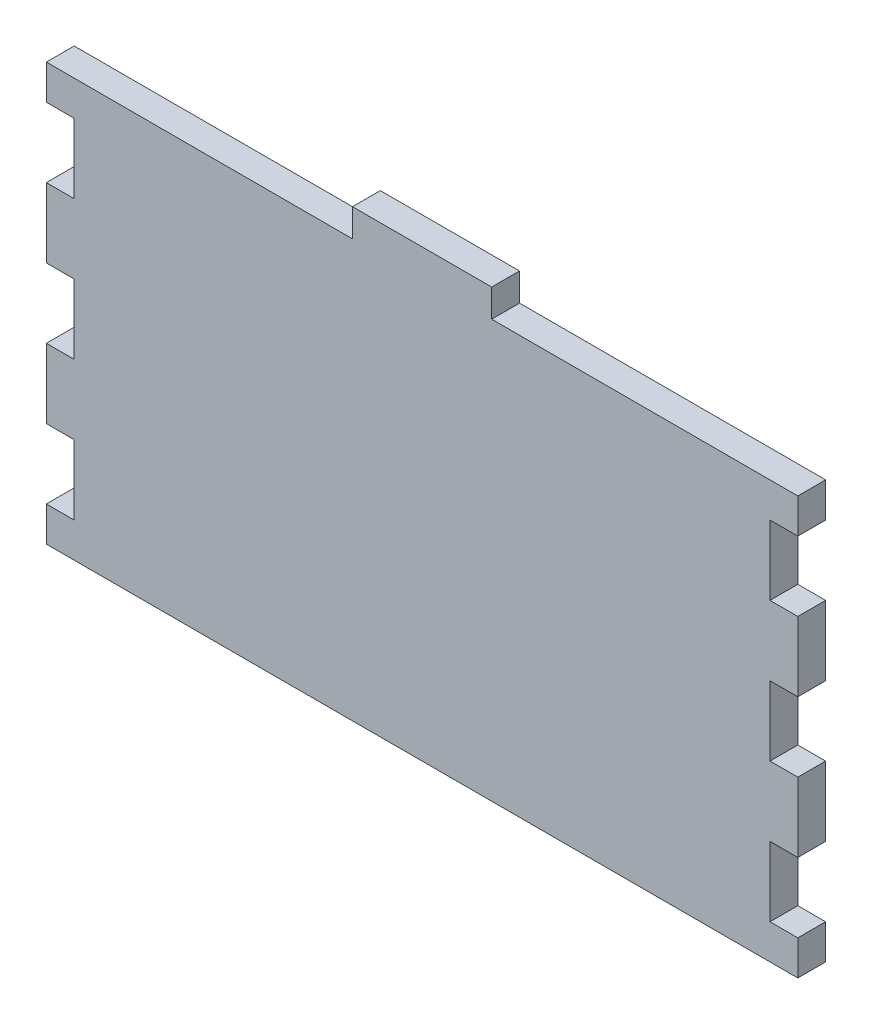
SolidWorks part; units mm, degrees
ref_plane "Front Plane" through (0, 0, 0) normal (0, 0, 1) x (1, 0, 0)
ref_plane "Top Plane" through (0, 0, 0) normal (0, 1, 0) x (1, 0, 0)
ref_plane "Right Plane" through (0, 0, 0) normal (1, 0, 0) x (0, 0, -1)
sketch "Sketch1" plane through (0, 0, 0) normal (0, 0, 1) x (1, 0, 0)
  line L0 (-50, 30) -> (-40, 30)
  line L1 (-50, -30) -> (50, -30)
  line L2 (-50, -30) -> (-50, 30)
  line L3 (-50, 30) -> (50, 30)
  line L4 (50, -30) -> (50, 30)
  line L5 (0, 30) -> (0, -30) construction
  line L6 (-50, 0) -> (50, 0) construction
  line L7 (-40, 30) -> (-30, 30)
  line L8 (-30, 30) -> (-20, 30)
  line L9 (-20, 30) -> (-10, 30)
  line L10 (-10, 30) -> (0, 30)
  line L11 (0, 30) -> (10, 30)
  line L12 (10, 30) -> (20, 30)
  line L13 (20, 30) -> (30, 30)
  line L14 (30, 30) -> (40, 30)
  line L15 (40, 30) -> (50, 30)
  line L16 (50, 30) -> (50, 20)
  line L17 (50, 20) -> (50, 10)
  line L18 (50, 10) -> (50, 6.1062)
  line L19 (50, 6.1062) -> (50, 0)
  line L20 (50, 0) -> (50, -10)
  line L21 (50, -10) -> (50, -20)
  line L22 (50, -20) -> (50, -25.2212)
  line L23 (50, -25.2212) -> (50, -30)
  line L24 (-50, 30) -> (-50, 20)
  line L25 (-50, 20) -> (-50, 10)
  line L26 (-50, 10) -> (-50, -10)
  line L27 (-50, -10) -> (-50, -20)
  line L29 (-50, 30) -> (-54, 30)
  line L30 (-50, 30) -> (-50, 25)
  line L31 (-50, 25) -> (-54, 25)
  line L32 (-54, 30) -> (-54, 25)
  line L33 (-50, 15) -> (-54, 15)
  line L34 (-50, 15) -> (-50, 5)
  line L35 (-50, 5) -> (-54, 5)
  line L36 (-54, 15) -> (-54, 5)
  line L37 (-50, -5) -> (-54, -5)
  line L38 (-50, -5) -> (-50, -15)
  line L39 (-50, -15) -> (-54, -15)
  line L40 (-54, -5) -> (-54, -15)
  line L41 (-50, -30) -> (-54, -30)
  line L42 (-50, -30) -> (-50, -25)
  line L43 (-50, -25) -> (-54, -25)
  line L44 (-54, -30) -> (-54, -25)
  line L45 (50, 30) -> (54, 30)
  line L46 (50, 30) -> (50, 25)
  line L47 (50, 25) -> (54, 25)
  line L48 (54, 30) -> (54, 25)
  line L65 (50, 15) -> (54, 15)
  line L66 (50, 15) -> (50, 5)
  line L67 (50, 5) -> (54, 5)
  line L68 (54, 15) -> (54, 5)
  line L69 (50, -5) -> (54, -5)
  line L70 (50, -5) -> (50, -15)
  line L71 (50, -15) -> (54, -15)
  line L72 (54, -5) -> (54, -15)
  line L73 (50, -30) -> (54, -30)
  line L74 (50, -30) -> (50, -25)
  line L75 (50, -25) -> (54, -25)
  line L76 (54, -30) -> (54, -25)
  point P0 (0, 0)
  dimension "D1" = 60
  dimension "D2" = 100
  dimension "D3" = 10
  dimension "D4" = 10
  dimension "D5" = 10
  dimension "D6" = 10
  dimension "D7" = 10
  dimension "D8" = 10
  dimension "D9" = 10
  dimension "D10" = 10
  dimension "D11" = 10
  dimension "D12" = 0
  dimension "D13" = 10
  dimension "D14" = 10
  dimension "D15" = 10
  dimension "D16" = 10
  dimension "D17" = 10
  dimension "D18" = 10
  dimension "D19" = 10
  dimension "D20" = 10
  dimension "D21" = 4
  dimension "D22" = 4
  dimension "D23" = 4
  dimension "D24" = 4
  dimension "D25" = 5
  dimension "D26" = 5
  dimension "D27" = 10
  dimension "D28" = 10
  dimension "D29" = 10
  dimension "D30" = 10
  dimension "D31" = 10
  dimension "D32" = 4
  dimension "D33" = 4
  dimension "D34" = 4
  dimension "D35" = 4
  dimension "D36" = 5
  dimension "D37" = 10
  dimension "D38" = 10
  dimension "D39" = 5
  dimension "D40" = 10
  dimension "D41" = 10
  dimension "D42" = 10
extrude "Boss-Extrude1" add sketch "Sketch1" along normal blind 4 contours L1 L4 L22 L21 L20 L19 L17 L16 L3 L0 L24 L2 L25 L26 L27 | L33 L36 L35 L26 L2 | L29 L32 L31 L24 | L37 L40 L39 L27 L2 | L44 L41 L2 L43 | L68 L65 L4 L19 L67 | L48 L45 L16 L47 | L72 L69 L4 L21 L71 | L73 L76 L75 L4
sketch "Sketch2" plane through (0, 0, 4) normal (0, 0, 1) x (1, 0, 0)
  line L0 (-54, 30) -> (54, 30)
  line L2 (-10, 26) -> (10, 26)
  line L3 (-10, 26) -> (-10, 34)
  line L4 (-10, 34) -> (10, 34)
  line L5 (10, 26) -> (10, 34)
  line L6 (0, 34) -> (0, 26) construction
  line L7 (-10, 30) -> (10, 30) construction
  point P4 (0, 30)
  dimension "D1" = 8
  dimension "D2" = 20
extrude "Boss-Extrude2" add sketch "Sketch2" against normal blind 4 contours L0 L5 L4 L3
